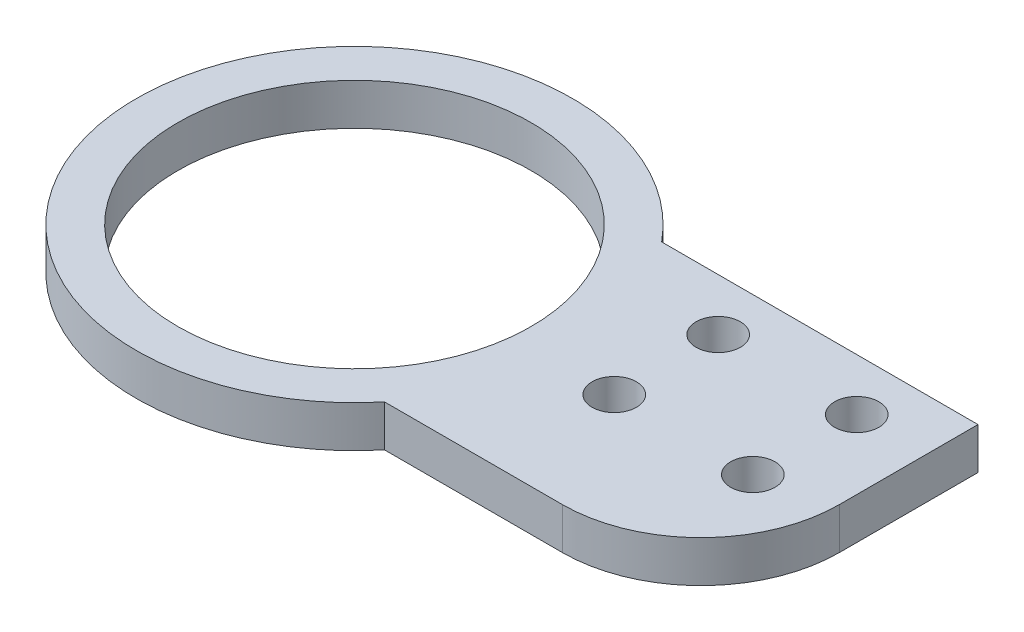
SolidWorks part; units mm, degrees
ref_plane "前视基准面" through (0, 0, 0) normal (0, 0, 1) x (1, 0, 0)
ref_plane "上视基准面" through (0, 0, 0) normal (0, 1, 0) x (1, 0, 0)
ref_plane "右视基准面" through (0, 0, 0) normal (1, 0, 0) x (0, 0, -1)
other "Configuration Table"
sketch "草图1" plane through (0, 0, 0) normal (0, 1, 0) x (1, 0, 0)
  line L1 (-27.5, -10) -> (27.5, -10)
  line L2 (-27.5, -10) -> (-27.5, 10)
  line L3 (-27.5, 10) -> (27.5, 10)
  line L4 (27.5, -10) -> (27.5, 10)
  line L5 (-27.5, -10) -> (27.5, 10) construction
  line L6 (-27.5, 10) -> (27.5, -10) construction
  point P0 (0, 0)
  dimension "D1" = 20
  dimension "D2" = 55
extrude "凸台-拉伸1" add sketch "草图1" along normal blind 3
sketch "草图2" plane through (0, 3, 0) normal (0, 1, 0) x (1, 0, 0)
  line L0 (-27.5, -10) -> (27.5, -10) construction
  line L1 (-27.5, 10) -> (2.5, 10)
  line L2 (-27.5, 10) -> (-27.5, -10)
  line L3 (-27.5, -10) -> (2.5, -10)
  line L4 (2.5, 10) -> (2.5, -10)
  line L5 (-7.5, 0) -> (-7.5, -9.5) construction
  line L6 (-7.5, 0) -> (0.7272, 4.75) construction
  line L7 (-7.5, 0) -> (-15.7272, 4.75) construction
  circle A0 centre (-7.5, 0) radius 9.5 construction
  circle A1 centre (-15.7272, 4.75) radius 1.6
  circle A2 centre (-7.5, -9.5) radius 1.6
  circle A3 centre (0.7272, 4.75) radius 1.6
  circle A4 centre (-7.5, 0) radius 6.75
  dimension "D2" = 19
  dimension "D5" = 3.2
  dimension "D7" = 13.5
  dimension "D1" = 30
  dimension "D3" = 120
  dimension "D4" = 120
  dimension "D6" = 10
  dimension "D8" = 20
extrude "切除-拉伸1" cut sketch "草图2" against normal through all contours A1 | A2 | A3 | A4
sketch "草图3" plane through (0, 3, 0) normal (0, 1, 0) x (1, 0, 0)
  line L1 (30, 10) -> (0, 10)
  line L2 (30, 10) -> (30, -10)
  line L3 (30, -10) -> (0, -10)
  line L4 (0, 10) -> (0, -10)
  dimension "D1" = 30
  dimension "D2" = 20
sketch "草图4" plane through (0, 3, 0) normal (0, 1, 0) x (1, 0, 0)
  line L0 (30, -10) -> (0, -10) construction
  line L1 (27.5, 10) -> (17.5, 10) construction
  line L2 (27.5, 10) -> (27.5, -10) construction
  line L3 (27.5, -10) -> (17.5, -10) construction
  line L4 (17.5, 10) -> (17.5, -10) construction
  line L6 (17.5, 10) -> (17.5, -5) construction
  circle A0 centre (22.5, 6.25) radius 1.6
  circle A1 centre (12.5, 6.25) radius 1.6
  circle A2 centre (22.5, -1.25) radius 1.6
  circle A3 centre (12.5, -1.25) radius 1.6
  dimension "D2" = 3.2
  dimension "D1" = 10
  dimension "D3" = 5
  dimension "D4" = 3.75
  dimension "D5" = 7.5
  dimension "D6" = 10
  dimension "D7" = 7.5
extrude "切除-拉伸2" cut sketch "草图4" against normal through all
sketch "草图5" plane through (0, 3, 0) normal (0, 1, 0) x (1, 0, 0)
  line L0 (-27.5, -10) -> (-27.5, -13)
  line L1 (-27.5, -13) -> (0, -13)
  line L3 (-27.5, -10) -> (27.5, -10)
  line L4 (27.5, -10) -> (27.5, -13)
  line L5 (27.5, -13) -> (0, -13)
  line L6 (27.5, -10) -> (27.5, 10) construction
  dimension "D1" = 3
extrude "凸台-拉伸2" add sketch "草图5" against normal blind 3
sketch "草图6" plane through (0, 3, 0) normal (0, 1, 0) x (1, 0, 0)
  circle A0 centre (-7.5, -9.5) radius 1.6
  dimension "D1" = 3.2
extrude "切除-拉伸3" cut sketch "草图6" against normal through all
sketch "草图7" plane through (0, 3, 0) normal (0, 1, 0) x (1, 0, 0)
  line L0 (-27.5, -13) -> (27.5, -13) construction
  line L1 (-27.5, 10) -> (-19.5, 10)
  line L2 (-27.5, 10) -> (-27.5, -13)
  line L3 (-27.5, -13) -> (-19.5, -13)
  line L4 (-19.5, 10) -> (-19.5, -13)
  dimension "D1" = 8
extrude "切除-拉伸4" cut sketch "草图7" against normal through all
sketch "草图8" plane through (0, 3, 0) normal (0, 1, 0) x (1, 0, 0)
  circle A0 centre (-7.5, 0) radius 12.75
  circle A1 centre (-7.5, 0) radius 15.75
  dimension "D1" = 25.5
  dimension "D2" = 3
sketch "草图9" plane through (0, 3, 0) normal (0, 1, 0) x (1, 0, 0)
  circle A0 centre (-7.5, 0) radius 18.064
extrude "凸台-拉伸4" add sketch "草图9" against normal blind 3
sketch "草图10" plane through (0, 3, 0) normal (0, 1, 0) x (1, 0, 0)
  circle A0 centre (-7.5, 0) radius 12.75
extrude "切除-拉伸6" cut sketch "草图10" against normal through all
sketch "草图11" plane through (0, 3, 0) normal (0, 1, 0) x (1, 0, 0)
  line L0 (27.5, 10) -> (4.6681, 10)
  line L1 (30, 10) -> (0, 10) construction
  line L2 (27.5, 10) -> (27.5, -13)
  line L3 (27.5, -13) -> (1.3917, -13)
  arc A0 (4.6681, 10) -> (1.3917, -13) centre (-7.5, 0) ccw
extrude "切除-拉伸7" cut sketch "草图11" against normal through all flip side to cut
sketch "草图12" plane through (0, 3, 0) normal (0, 1, 0) x (1, 0, 0)
  line L0 (27.5, 10) -> (27.5, -10)
  line L1 (30, -10) -> (0, -10) construction
  line L2 (27.5, -13) -> (27.5, 10) construction
  line L3 (27.5, 10) -> (4.6681, 10)
  line L4 (27.5, -10) -> (4.6681, -10)
  arc A0 (4.6681, 10) -> (4.6681, -10) centre (-7.5, 0) ccw
extrude "切除-拉伸8" cut sketch "草图12" against normal through all flip side to cut
fillet "圆角1" radius 10 1 edges at (27.5, 1.5, 10)
